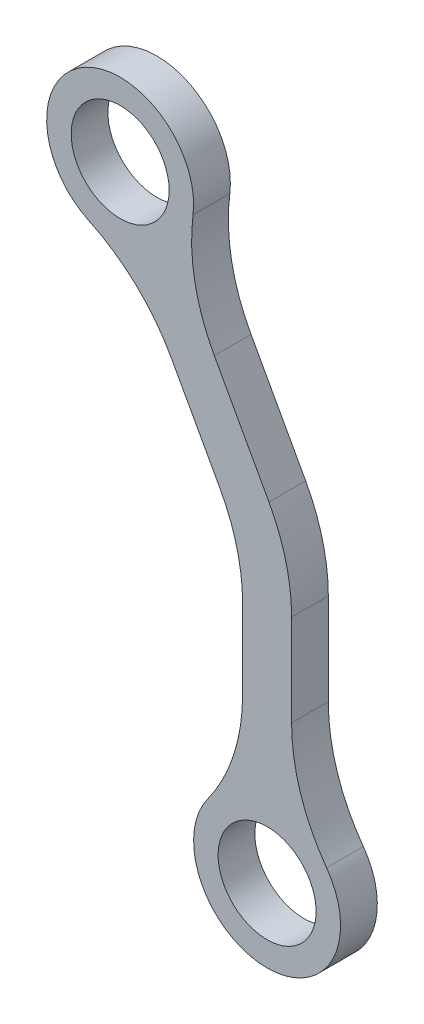
SolidWorks part; units mm, degrees
material "ABS"
ref_plane "Front Plane" through (0, 0, 0) normal (0, 0, 1) x (1, 0, 0)
ref_plane "Top Plane" through (0, 0, 0) normal (0, 1, 0) x (1, 0, 0)
ref_plane "Right Plane" through (0, 0, 0) normal (1, 0, 0) x (0, 0, -1)
sketch "Sketch1" plane through (0, 0, 0) normal (0, 0, 1) x (1, 0, 0)
  line L0 (-2, 5.6569) -> (-2, 22.631)
  line L1 (2, 5.6569) -> (2, 23.6569)
  line L2 (0, 23.1439) -> (-12, 45) construction
  line L3 (-2, 22.631) -> (-11.0306, 39.0788)
  line L4 (2, 23.6569) -> (-7.5243, 41.0039)
  line L5 (0, 0) -> (0, 23.1439) construction
  line L6 (-11.0306, 39.0788) -> (-7.5243, 41.0039) construction
  line L7 (-2, 5.6569) -> (2, 5.6569) construction
  circle A0 centre (0, 0) radius 4
  arc A1 (-7.5243, 41.0039) -> (-11.0306, 39.0788) centre (-12, 45) ccw
  arc A2 (-2, 5.6569) -> (2, 5.6569) centre (0, 0) ccw
  circle A3 centre (-12, 45) radius 4
  dimension "D1" = 8
  dimension "D2" = 4
  dimension "D11" = 2
  dimension "D3" = 45
  dimension "D5" = 12
  dimension "D8" = 18
extrude "Boss-Extrude1" add sketch "Sketch1" along normal mid plane 3
fillet "Fillet3" radius 15 6 edges at (2, 5.6569, 0) (2, 23.6569, 0) (-7.5243, 41.0039, 0) (-2, 5.6569, 0) (-2, 22.631, 0) (-11.0306, 39.0788, 0)
